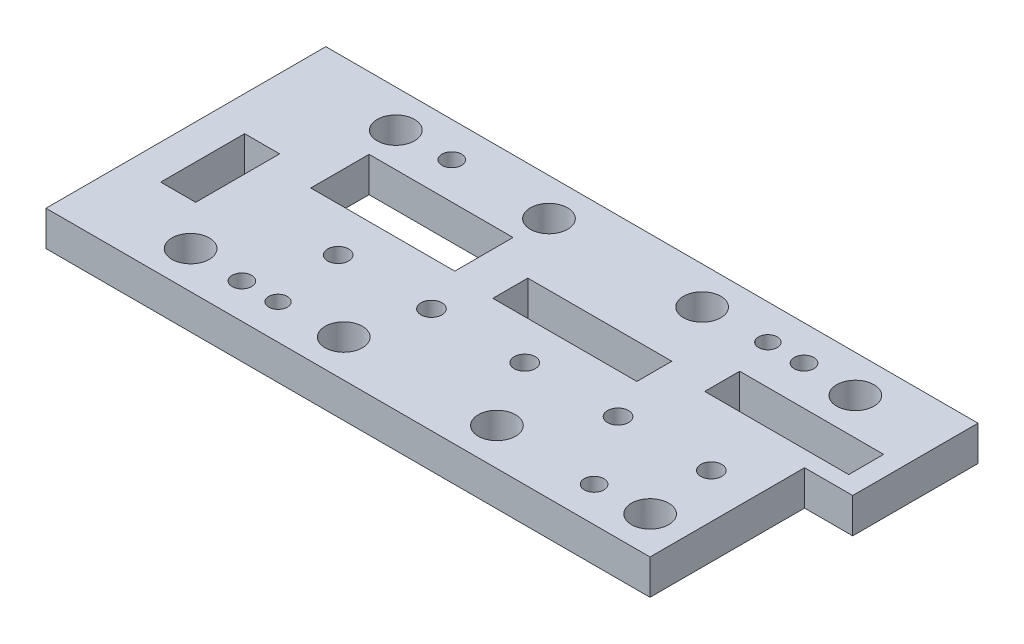
SolidWorks part; units mm, degrees
material "Plain Carbon Steel"
ref_plane "Front Plane" through (0, 0, 0) normal (0, 0, 1) x (1, 0, 0)
ref_plane "Top Plane" through (0, 0, 0) normal (0, 1, 0) x (1, 0, 0)
ref_plane "Right Plane" through (0, 0, 0) normal (1, 0, 0) x (0, 0, -1)
sketch "Sketch1" plane through (0, 0, 0) normal (0, 1, 0) x (1, 0, 0)
  line L0 (-229, 60) -> (-229, -60) construction
  line L1 (-229, -60) -> (0, -60)
  line L2 (-229, -60) -> (-229, 60)
  line L3 (-229, 60) -> (0, 60)
  line L4 (0, -60) -> (0, 60)
  point P4 (0, 0)
  dimension "D1" = 120
extrude "Boss-Extrude1" add sketch "Sketch1" along normal mid plane 15
ref_plane "Plane2" through (-114.5, 0, 0) normal (1, 0, 0) x (0, 0, -1)
sketch "Sketch4" plane through (0, 7.5, 0) normal (0, 1, 0) x (1, 0, 0)
  line L1 (0, 60) -> (20.6325, 60)
  line L2 (0, 60) -> (0, 6.27)
  line L3 (0, 6.27) -> (20.6325, 6.27)
  line L4 (20.6325, 60) -> (20.6325, 6.27)
extrude "Boss-Extrude2" add sketch "Sketch4" against normal up to surface (15 mm away) up to face at (-114.5, -7.5, 0)
sketch "Sketch5" plane through (0, 7.5, 0) normal (0, 1, 0) x (1, 0, 0)
  line L1 (-129.75, 17.3524) -> (-68, 17.3524)
  line L2 (-129.75, 17.3524) -> (-129.75, 2.3524)
  line L3 (-129.75, 2.3524) -> (-68, 2.3524)
  line L4 (-68, 17.3524) -> (-68, 2.3524)
  line L5 (-49.75, 28.191) -> (12, 28.191)
  line L6 (-49.75, 28.191) -> (-49.75, 13.191)
  line L7 (-49.75, 13.191) -> (12, 13.191)
  line L8 (12, 28.191) -> (12, 13.191)
  line L9 (-209.75, 29.28) -> (-148, 29.28)
  line L10 (-209.75, 29.28) -> (-209.75, 4.28)
  line L11 (-209.75, 4.28) -> (-148, 4.28)
  line L12 (-148, 29.28) -> (-148, 4.28)
extrude "Cut-Extrude1" cut sketch "Sketch5" against normal up to next
sketch "Sketch8" plane through (0, 7.5, 0) normal (0, 1, 0) x (1, 0, 0)
  line L3 (-11, 0) -> (11, 0) construction
  line L4 (-114.5, -11) -> (-114.5, 11) construction
  circle A0 centre (-213, 44) radius 8
  dimension "D1" = 16
  dimension "D2" = 44
  dimension "D3" = 98.5
extrude "Cut-Extrude4" cut sketch "Sketch8" against normal up to next
pattern_linear "LPattern2" count 4 spacing 65.677 along (1, 0, 0) count 2 spacing 88 along (0, 0, 1) of "Cut-Extrude4"
hole_wizard "Ø9.0 (9) Diameter Hole1" positions "Sketch11" profile "Sketch10" hole size "Ø9.0" standard "ISO" end condition through all
sketch "Sketch11" plane through (0, 7.5, 0) normal (0, 1, 0) x (1, 0, 0)
  point P0 (-179, -14.72)
  point P3 (-139, -14.72)
  point P6 (-99, -14.72)
  point P9 (-59, -14.72)
  point P12 (-19, -14.72)
sketch "Sketch10" plane through (-179, 7.5, 14.72) normal (1, 0, 0) x (0, 0, 1)
  line L0 (0, 0) -> (0, 15)
  line L1 (0, 15) -> (4.5, 15)
  line L2 (4.5, 15) -> (4.5, 0)
  line L5 (4.5, 0) -> (0, 0)
  line L11 (0, -6.35) -> (0, 107.95) construction
  dimension "Thru Hole Dia." = 9
  dimension "Thru Hole Depth" = 15
hole_wizard "CBORE for M8 Hex Socket Head Cap Screw1" positions "Sketch14" profile "Sketch13" counterbore size "M8" standard "ISO" end condition through all
sketch "Sketch14" plane through (0, -7.5, 0) normal (0, -1, 0) x (-1, 0, 0)
  line L0 (-20.6325, 60) -> (229, 60) construction
  line L1 (229, -60) -> (0, -60) construction
  circle A0 centre (15.969, 44) radius 8 construction
  circle A1 centre (213, 44) radius 8 construction
  point P0 (38.969, 45)
  point P2 (190, 45)
  point P4 (190, -45)
  point P6 (38.969, -45)
  dimension "D1" = 15
  dimension "D2" = 15
  dimension "D3" = 15
  dimension "D4" = 15
sketch "Sketch13" plane through (-38.969, -7.5, -45) normal (1, 0, 0) x (0, 0, -1)
  line L0 (0, 0) -> (0, 15)
  line L1 (0, 15) -> (4.2, 15)
  line L3 (4.2, 15) -> (4.2, 8.6)
  line L4 (4.2, 8.6) -> (7.5, 8.6)
  line L5 (7.5, 8.6) -> (7.5, 0)
  line L7 (7.5, 0) -> (0, 0)
  line L11 (0, -6.35) -> (0, 107.95) construction
  dimension "Thru Hole Dia." = 8.4
  dimension "Thru Hole Depth" = 15
  dimension "C'Bore Dia." = 15
  dimension "C'Bore Depth" = 8.6
hole_wizard "Ø8.0mm Dowel Hole1" positions "Sketch17" profile "Sketch16" hole size "Ø8.0" standard "ISO" end condition through all
sketch "Sketch17" plane through (0, -7.5, 0) normal (0, -1, 0) x (-1, 0, 0)
  line L0 (-20.6325, 60) -> (229, 60) construction
  line L1 (229, -60) -> (0, -60) construction
  circle A0 centre (190, -45) radius 7.5 construction
  circle A1 centre (38.969, 45) radius 7.5 construction
  point P0 (174.5, -45)
  point P2 (54.469, 45)
  dimension "D1" = 8
  dimension "D2" = 8
  dimension "D3" = 15
  dimension "D4" = 15
sketch "Sketch16" plane through (-174.5, -7.5, 45) normal (1, 0, 0) x (0, 0, -1)
  line L0 (0, 0) -> (0, 15)
  line L1 (0, 15) -> (4, 15)
  line L2 (4, 15) -> (4, 0)
  line L5 (4, 0) -> (0, 0)
  line L11 (0, -6.35) -> (0, 107.95) construction
  dimension "Thru Hole Dia." = 8
  dimension "Thru Hole Depth" = 15
sketch "Sketch18" plane through (-229, 0, 0) normal (-1, 0, 0) x (0, 0, 1)
  line L4 (-60, -7.5) -> (60, -7.5)
  line L5 (60, -7.5) -> (60, 7.5)
  line L6 (60, 7.5) -> (-60, 7.5)
  line L7 (-60, 7.5) -> (-60, -7.5)
  line L8 (-60, -7.5) -> (60, -7.5)
  line L9 (60, -7.5) -> (60, 7.5)
  line L10 (60, 7.5) -> (-60, 7.5)
  line L11 (-60, 7.5) -> (-60, -7.5)
  dimension "D1" = 0
extrude "Boss-Extrude3" add sketch "Sketch18" along normal blind 30
sketch "Sketch19" plane through (0, 7.5, 0) normal (0, 1, 0) x (1, 0, 0)
  line L4 (-229.1, -25.72) -> (-229.1, 10.28)
  line L5 (-229.1, 10.28) -> (-244.1, 10.28)
  line L6 (-244.1, 10.28) -> (-244.1, -25.72)
  line L7 (-244.1, -25.72) -> (-229.1, -25.72)
  line L8 (-229.1, -25.72) -> (-229.1, 10.28)
  line L9 (-229.1, 10.28) -> (-244.1, 10.28)
  line L10 (-244.1, 10.28) -> (-244.1, -25.72)
  line L11 (-244.1, -25.72) -> (-229.1, -25.72)
  dimension "D1" = 0
extrude "Cut-Extrude5" cut sketch "Sketch19" against normal up to next
